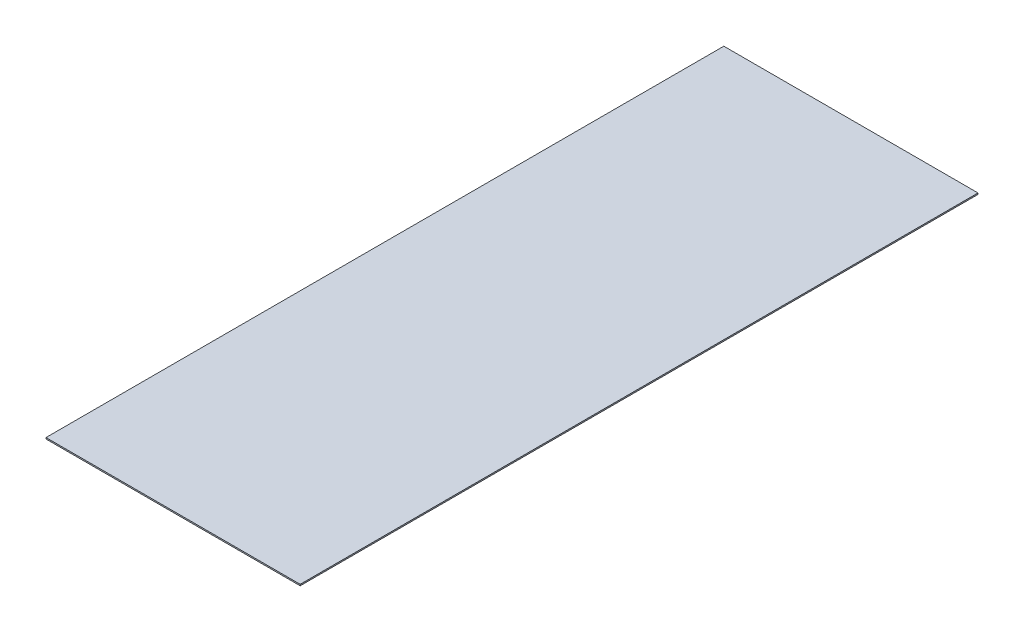
SolidWorks part; units mm, degrees
material "ASTM A36 Acero"
ref_plane "Alzado" through (0, 0, 0) normal (0, 0, 1) x (1, 0, 0)
ref_plane "Planta" through (0, 0, 0) normal (0, 1, 0) x (1, 0, 0)
ref_plane "Vista lateral" through (0, 0, 0) normal (1, 0, 0) x (0, 0, -1)
sketch "Croquis1" plane through (0, 0, 0) normal (0, 1, 0) x (1, 0, 0)
  line L1 (-457.2, -1219.2) -> (457.2, -1219.2)
  line L2 (-457.2, -1219.2) -> (-457.2, 1219.2)
  line L3 (-457.2, 1219.2) -> (457.2, 1219.2)
  line L4 (457.2, -1219.2) -> (457.2, 1219.2)
  line L5 (-457.2, -1219.2) -> (457.2, 1219.2) construction
  line L6 (-457.2, 1219.2) -> (457.2, -1219.2) construction
  point P0 (0, 0)
  dimension "D1" = 2438.4
  dimension "D2" = 914.4
extrude "Saliente-Extruir1" add sketch "Croquis1" along normal blind 4.8
